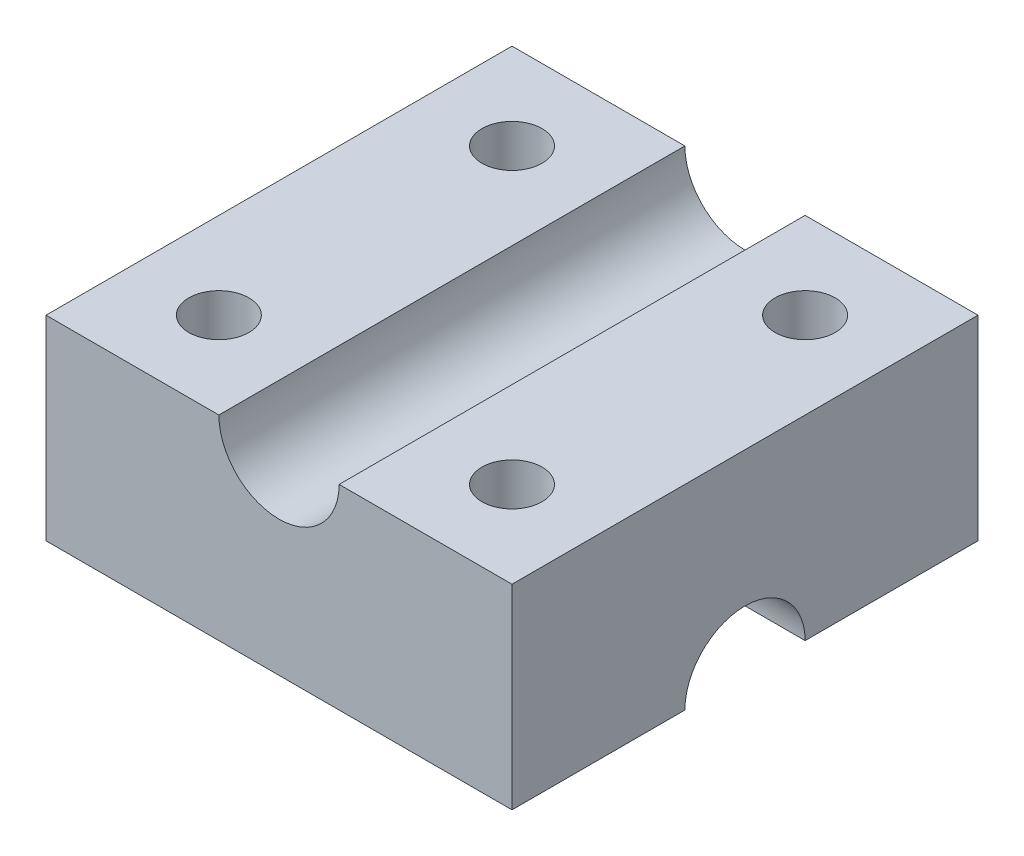
SolidWorks part; units mm, degrees
ref_plane "Přední rovina" through (0, 0, 0) normal (0, 0, 1) x (1, 0, 0)
ref_plane "Horní rovina" through (0, 0, 0) normal (0, 1, 0) x (1, 0, 0)
ref_plane "Pravá rovina" through (0, 0, 0) normal (1, 0, 0) x (0, 0, -1)
sketch "Skica1" plane through (0, 0, 0) normal (0, 0, 1) x (1, 0, 0)
  line L0 (0, 0) -> (15.5, 0) construction
  line L1 (0, 0) -> (0, 6.5) construction
  line L2 (-15.5, 6.5) -> (-4, 6.5)
  line L3 (15.5, 6.5) -> (15.5, -6.5)
  line L4 (-15.5, -6.5) -> (15.5, -6.5)
  line L5 (-15.5, 6.5) -> (-15.5, -6.5)
  line L6 (4, 6.5) -> (15.5, 6.5)
  arc A0 (-4, 6.5) -> (4, 6.5) centre (0, 6.5) ccw
  point P9 (0, -6.5)
  dimension "D3" = 8
  dimension "D1" = 31
  dimension "D2" = 13
extrude "Přidat vysunutím1" add sketch "Skica1" along normal blind 31
sketch "Skica2" plane through (-15.5, 0, 0) normal (-1, 0, 0) x (0, 0, 1)
  line L0 (31, -6.5) -> (0, -6.5) construction
  circle A0 centre (15.5, -6.5) radius 4
  dimension "D1" = 8
extrude "Odebrat vysunutím1" cut sketch "Skica2" against normal through all
sketch "Skica3" plane through (0, 6.5, 0) normal (0, 1, 0) x (1, 0, 0)
  line L0 (15.5, -15.5) -> (9.75, -15.5) construction
  line L1 (15.5, -31) -> (15.5, 0) construction
  line L2 (9.75, -15.5) -> (9.75, -5.75) construction
  line L3 (15.5, 0) -> (4, 0) construction
  line L4 (0, 0) -> (0, -31) construction
  line L7 (-4, -31) -> (4, -31) construction
  circle A0 centre (9.75, -5.75) radius 2
  circle A1 centre (9.75, -25.25) radius 2
  circle A3 centre (-9.75, -25.25) radius 2
  circle A4 centre (-9.75, -5.75) radius 2
  dimension "D3" = 4
  dimension "D1" = 5.75
  dimension "D2" = 5.75
extrude "Odebrat vysunutím2" cut sketch "Skica3" against normal through all
sketch "Skica4" plane through (-15.5, 0, 0) normal (-1, 0, 0) x (0, 0, 1)
  line L0 (15.5, 6.5) -> (15.5, 1.5) construction
  line L1 (31, 6.5) -> (0, 6.5) construction
  circle A0 centre (15.5, 1.5) radius 2
  dimension "D2" = 4
  dimension "D1" = 5
extrude "Odebrat vysunutím3" cut sketch "Skica4" against normal blind 10
